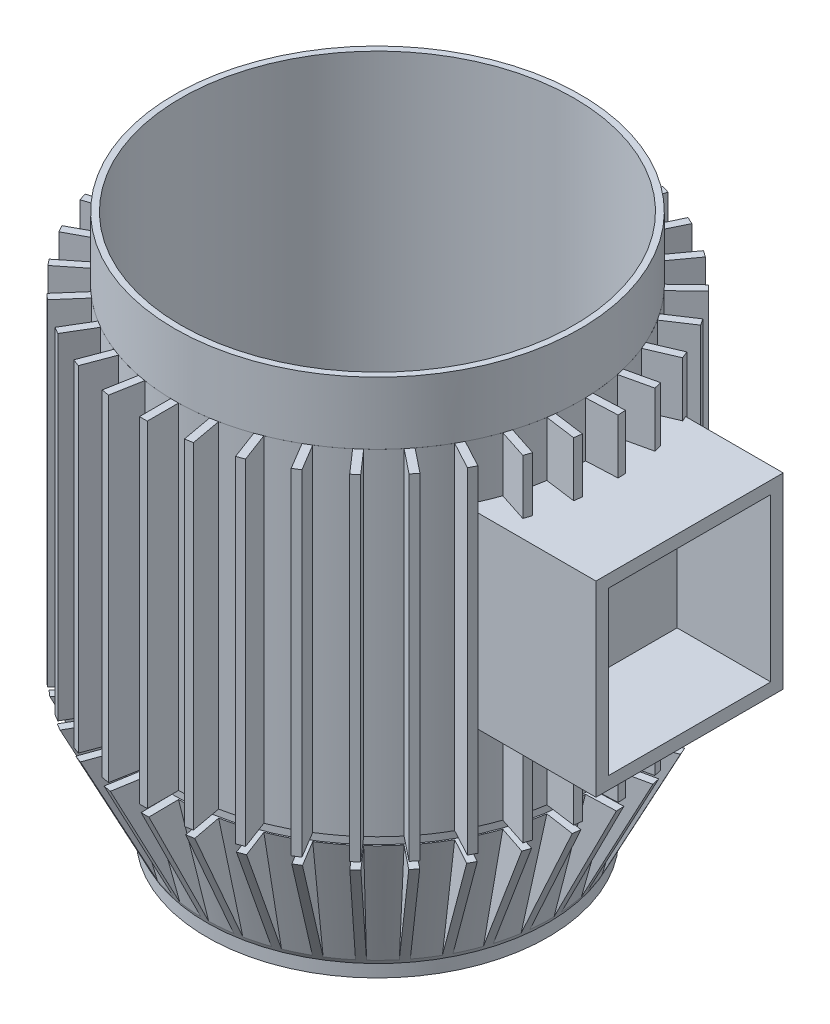
SolidWorks part; units mm, degrees
ref_plane "Front Plane" through (0, 0, 0) normal (0, 0, 1) x (1, 0, 0)
ref_plane "Top Plane" through (0, 0, 0) normal (0, 1, 0) x (1, 0, 0)
ref_plane "Right Plane" through (0, 0, 0) normal (1, 0, 0) x (0, 0, -1)
sketch "Sketch1" plane through (0, 0, 0) normal (0, 1, 0) x (1, 0, 0)
  circle A0 centre (0, 0) radius 65
  dimension "D1" = 130
extrude "Boss-Extrude1" add sketch "Sketch1" against normal blind 170
chamfer "Chamfer1" distance 10 distance2 40 1 edges at (0, -170, 65)
shell "Shell1" thickness 2
ref_plane "Plane1" through (0, 0, 75) normal (0, 0, 1) x (1, 0, 0)
sketch "Sketch2" plane through (0, 0, 75) normal (0, 0, 1) x (1, 0, 0)
  line L0 (65, 0) -> (-65, 0) construction
  line L1 (-1.25, 0) -> (1.25, 0)
  line L2 (-1.25, 0) -> (-1.25, -170)
  line L3 (-1.25, -170) -> (1.25, -170)
  line L4 (1.25, 0) -> (1.25, -170)
  line L5 (-55, -170) -> (55, -170) construction
  line L6 (0, 0) -> (0, -170) construction
  dimension "D1" = 2.5
extrude "Boss-Extrude2" add sketch "Sketch2" against normal up to next
pattern_circular "CirPattern1" count 35 over 360 about axis through (0, 0, 0) along (0, 1, 0) of "Boss-Extrude2"
sketch "Sketch3" plane through (0, 0, 0) normal (0, 0, 1) x (1, 0, 0)
  line L0 (54.656, -170) -> (74.489, -130.1194)
  line L1 (74.489, -170) -> (74.489, 0) construction
  line L2 (54.656, -170) -> (90.451, -179.2784)
  line L3 (90.451, -179.2784) -> (90.451, -127.5)
  line L4 (90.451, -127.5) -> (64.5676, -127.5)
  line L5 (64.5676, 0) -> (64.5676, -130) construction
  line L6 (64.5676, -127.5) -> (64.5676, -130)
  line L7 (64.5676, -130) -> (74.489, -130.1194)
  line L8 (0, 0) -> (0, -216.905) construction
  line L9 (63, 0) -> (-63, 0) construction
  dimension "D1" = 2.5
revolve "Cut-Revolve1" cut sketch "Sketch3" angle 360 about L8
sketch "Sketch4" plane through (0, -170, 0) normal (0, -1, 0) x (1, 0, 0)
  circle A0 centre (0, 0) radius 10
  dimension "D1" = 20
extrude "Cut-Extrude1" cut sketch "Sketch4" against normal through all
ref_plane "Plane2" through (100, 0, 0) normal (1, 0, 0) x (0, 0, -1)
sketch "Sketch5" plane through (100, 0, 0) normal (1, 0, 0) x (0, 0, -1)
  line L0 (0, 0) -> (0, -176.5661) construction
  line L1 (-18.8936, -127.5) -> (-9.9622, -127.5) construction
  line L2 (-30, -37.5) -> (30, -37.5)
  line L3 (-30, -37.5) -> (-30, -97.5)
  line L4 (-30, -97.5) -> (30, -97.5)
  line L5 (30, -37.5) -> (30, -97.5)
  dimension "D1" = 60
  dimension "D2" = 60
  dimension "D3" = 30
extrude "Boss-Extrude3" add sketch "Sketch5" against normal up to next
sketch "Sketch6" plane through (100, 0, 0) normal (1, 0, 0) x (0, 0, -1)
  line L16 (-26, -41.5) -> (-26, -93.5)
  line L17 (-26, -93.5) -> (26, -93.5)
  line L18 (26, -93.5) -> (26, -41.5)
  line L19 (26, -41.5) -> (-26, -41.5)
  line L20 (-26, -41.5) -> (-26, -93.5)
  line L21 (-26, -93.5) -> (26, -93.5)
  line L22 (26, -93.5) -> (26, -41.5)
  line L23 (26, -41.5) -> (-26, -41.5)
  dimension "D1" = 4
extrude "Cut-Extrude2" cut sketch "Sketch6" against normal blind 30
sketch "Sketch7" plane through (0, 0, 0) normal (1, 0, 0) x (0, 0, -1)
  line L0 (-64.988, -127.5) -> (-64.988, 0) construction
  line L1 (-80.5547, 0) -> (-64.988, 0)
  line L2 (-80.5547, 0) -> (-80.5547, -20)
  line L3 (-80.5547, -20) -> (-64.988, -20)
  line L4 (-64.988, 0) -> (-64.988, -20)
  line L5 (0, 35.7548) -> (0, -66.4022) construction
  dimension "D1" = 20
revolve "Cut-Revolve2" cut sketch "Sketch7" angle 360 about L5
sketch "草图1" plane through (0, -170, 0) normal (0, -1, 0) x (1, 0, 0)
  circle A0 centre (0, 0) radius 54.656
extrude "凸台-拉伸1" add sketch "草图1" along normal blind 4
